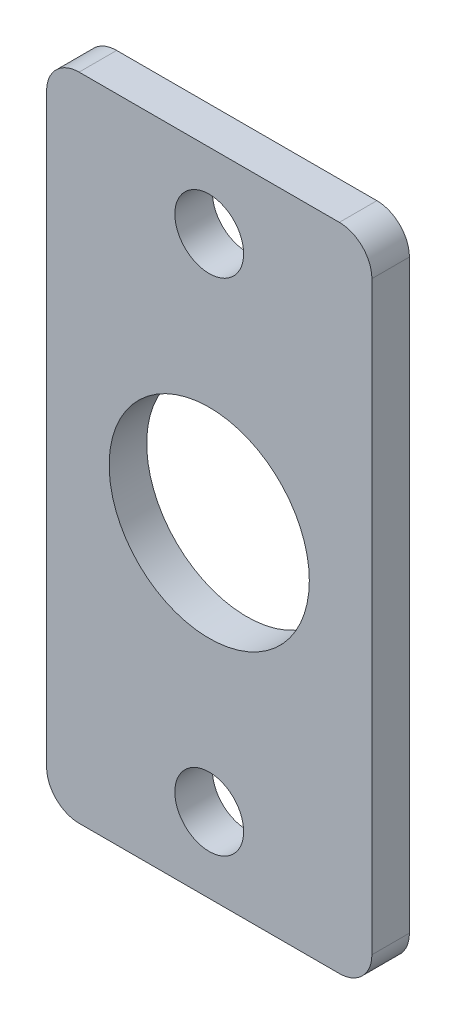
SolidWorks part; units mm, degrees
ref_plane "前视基准面" through (0, 0, 0) normal (0, 0, 1) x (1, 0, 0)
ref_plane "上视基准面" through (0, 0, 0) normal (0, 1, 0) x (1, 0, 0)
ref_plane "右视基准面" through (0, 0, 0) normal (1, 0, 0) x (0, 0, -1)
sketch "草图1" plane through (0, 0, 0) normal (0, 0, 1) x (1, 0, 0)
  line L0 (0, 26) -> (0, -26) construction
  line L1 (-13, -26) -> (13, -26)
  line L2 (-13, -26) -> (-13, 26)
  line L3 (-13, 26) -> (13, 26)
  line L4 (13, -26) -> (13, 26)
  line L5 (-13, -26) -> (13, 26) construction
  line L6 (-13, 26) -> (13, -26) construction
  line L7 (0, 0) -> (-13, 0) construction
  line L8 (0, 0) -> (3, 0) construction
  circle A0 centre (0, 20) radius 2.75
  circle A1 centre (0, 0) radius 8
  circle A2 centre (-9, 20) radius 2.75
  point P0 (0, 0)
  point P8 (0, 20)
  point P13 (-9, 20)
  point P14 (9, 20)
  dimension "BP" = 5.5
  dimension "L" = 16
  dimension "BE" = 52
  dimension "BC" = 26
  dimension "BF" = 40
  dimension "BD" = 18
  dimension "BB" = 3
sketch "草图2" plane through (0, 0, 0) normal (0, 0, 1) x (1, 0, 0)
  line L0 (13, -26) -> (13, 26) construction
  line L1 (-13, -26) -> (13, -26) construction
  line L2 (-13, -26) -> (-13, 26) construction
  line L3 (-13, 26) -> (13, 26) construction
  line L4 (13, -26) -> (13, 26)
  line L5 (-13, -26) -> (13, -26)
  line L6 (-13, -26) -> (-13, 26)
  line L7 (-13, 26) -> (13, 26)
extrude "凸台-拉伸1" add sketch "草图2" along normal blind 3
sketch "草图4" plane through (0, 0, 3) normal (0, 0, 1) x (1, 0, 0)
  circle A0 centre (0, 0) radius 8 construction
  circle A1 centre (0, 0) radius 8
extrude "切除-拉伸2" cut sketch "草图4" against normal through all
fillet "圆角1" radius 2.6 4 edges at (13, -26, 1.5) (-13, -26, 1.5) (-13, 26, 1.5) (13, 26, 1.5)
sketch "草图3" plane through (0, 0, 3) normal (0, 0, 1) x (1, 0, 0)
  line L0 (0, 0) -> (-13, 0) construction
  circle A0 centre (0, 20) radius 2.75 construction
  circle A1 centre (0, 20) radius 2.75
  circle A2 centre (0, -20) radius 2.75
extrude "16" cut sketch "草图3" against normal through all
sketch "草图5" plane through (0, 0, 3) normal (0, 0, 1) x (1, 0, 0)
  line L0 (0, 0) -> (-13, 0) construction
  line L1 (0, 0) -> (0, 26) construction
  circle A0 centre (-9, 20) radius 2.75 construction
  circle A1 centre (-9, 20) radius 2.75
  circle A2 centre (9, 20) radius 2.75
  circle A3 centre (9, -20) radius 2.75
  circle A4 centre (-9, -20) radius 2.75
extrude "32" [suppressed] cut sketch "草图5" against normal through all
equation "\"D1@凸台-拉伸1\" = \"BB@草图1\""
equation "\"D1@圆角1\" = \"BC@草图1\"*0.1"
